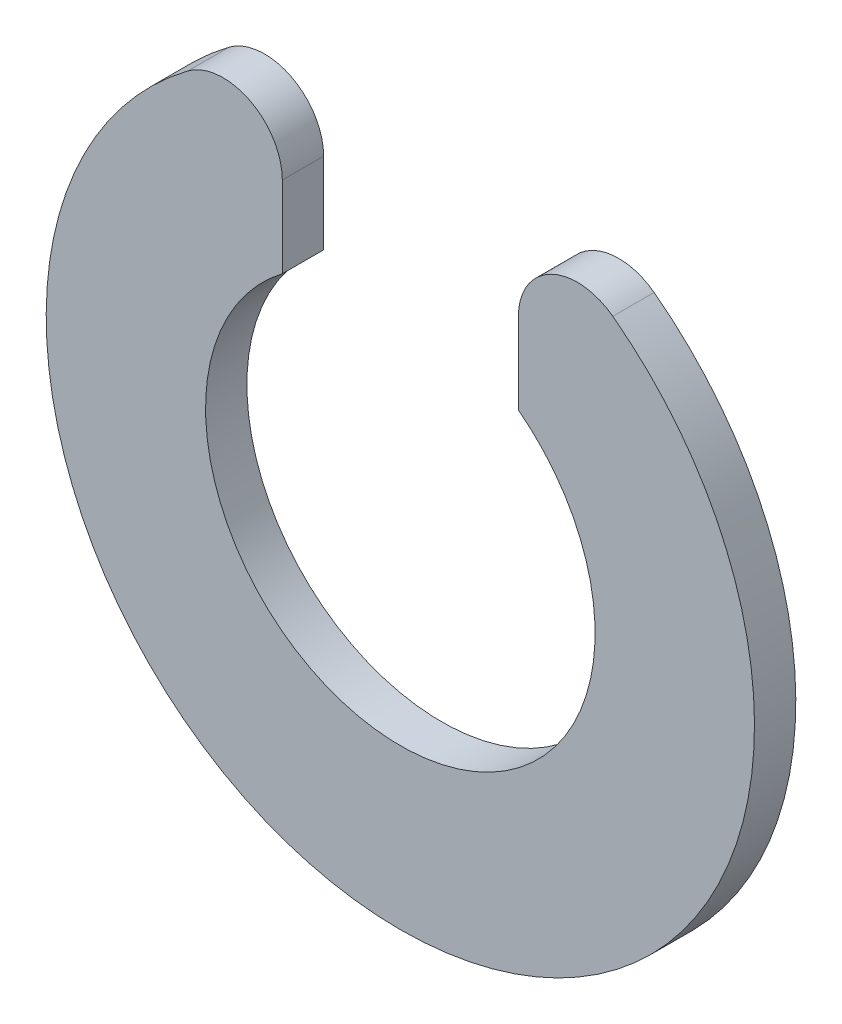
SolidWorks part; units mm, degrees
material "Plain Carbon Steel"
ref_plane "Front Plane" through (0, 0, 0) normal (0, 0, 1) x (1, 0, 0)
ref_plane "Top Plane" through (0, 0, 0) normal (0, 1, 0) x (1, 0, 0)
ref_plane "Right Plane" through (0, 0, 0) normal (1, 0, 0) x (0, 0, -1)
sketch "Sketch1" plane through (0, 0, 0) normal (0, 0, 1) x (1, 0, 0)
  circle A0 centre (0, 0) radius 3.3
  circle A1 centre (0, 0) radius 6
  dimension "D1" = 6.6
  dimension "D2" = 12
extrude "Boss-Extrude1" add sketch "Sketch1" along normal blind 0.7
sketch "Sketch2" plane through (0, 0, 0.7) normal (0, 0, 1) x (1, 0, 0)
  line L0 (-2, 5.6569) -> (-2, 2.6249)
  line L1 (-2, 2.6249) -> (2, 2.6249)
  line L2 (2, 2.6249) -> (2, 5.6569)
  circle A0 centre (0, 0) radius 6 construction
  circle A1 centre (0, 0) radius 3.3 construction
  arc A2 (2, 5.6569) -> (-2, 5.6569) centre (0, 5.6569) ccw
  dimension "D1" = 4
extrude "Cut-Extrude1" cut sketch "Sketch2" against normal up to vertex (0.7 mm away) up to point (0, 0, 0)
fillet "Fillet1" radius 1 2 edges at (2, 5.6569, 0.35) (-2, 5.6569, 0.35)
